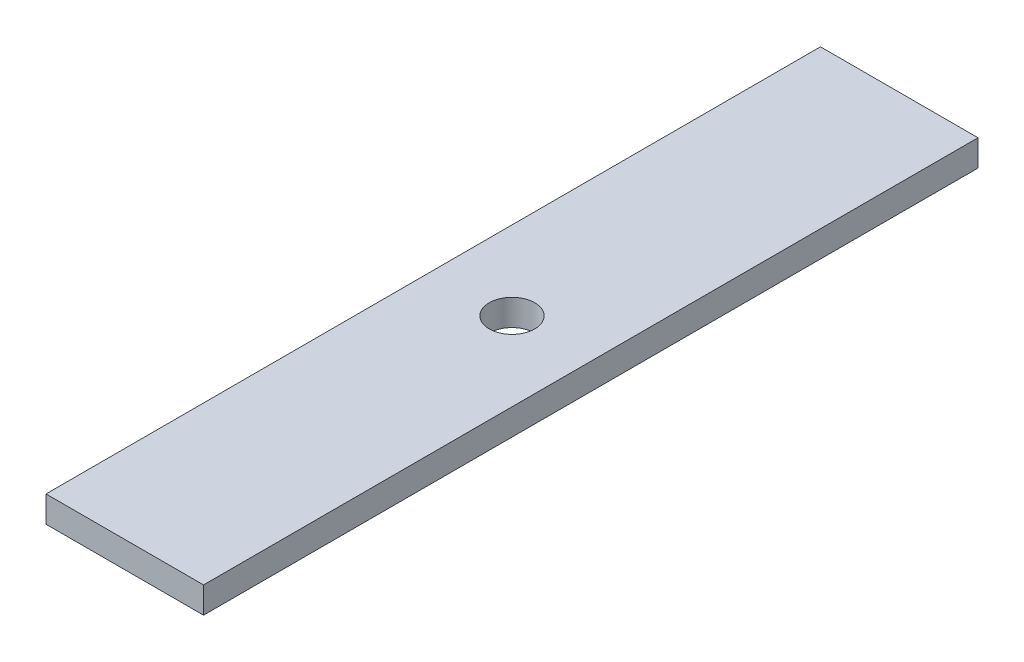
SolidWorks part; units mm, degrees
ref_plane "Front Plane" through (0, 0, 0) normal (0, 0, 1) x (1, 0, 0)
ref_plane "Top Plane" through (0, 0, 0) normal (0, 1, 0) x (1, 0, 0)
ref_plane "Right Plane" through (0, 0, 0) normal (1, 0, 0) x (0, 0, -1)
sketch "Sketch1" plane through (0, 0, 0) normal (0, 0, 1) x (1, 0, 0)
  line L1 (-9.525, -1.5875) -> (9.525, -1.5875)
  line L2 (-9.525, -1.5875) -> (-9.525, 1.5875)
  line L3 (-9.525, 1.5875) -> (9.525, 1.5875)
  line L4 (9.525, -1.5875) -> (9.525, 1.5875)
  line L5 (-9.525, -1.5875) -> (9.525, 1.5875) construction
  line L6 (-9.525, 1.5875) -> (9.525, -1.5875) construction
  point P0 (0, 0)
  dimension "D1" = 3.175
  dimension "D2" = 19.05
extrude "Boss-Extrude1" add sketch "Sketch1" along normal blind 93.65
sketch "Sketch2" plane through (0, 1.5875, 0) normal (0, 1, 0) x (1, 0, 0)
  line L0 (0, 0) -> (0, -93.65) construction
  line L1 (9.525, -93.65) -> (-9.525, -93.65) construction
  circle A0 centre (0, -46.825) radius 2.75
  dimension "D1" = 5.5
extrude "Cut-Extrude1" cut sketch "Sketch2" against normal blind 10
